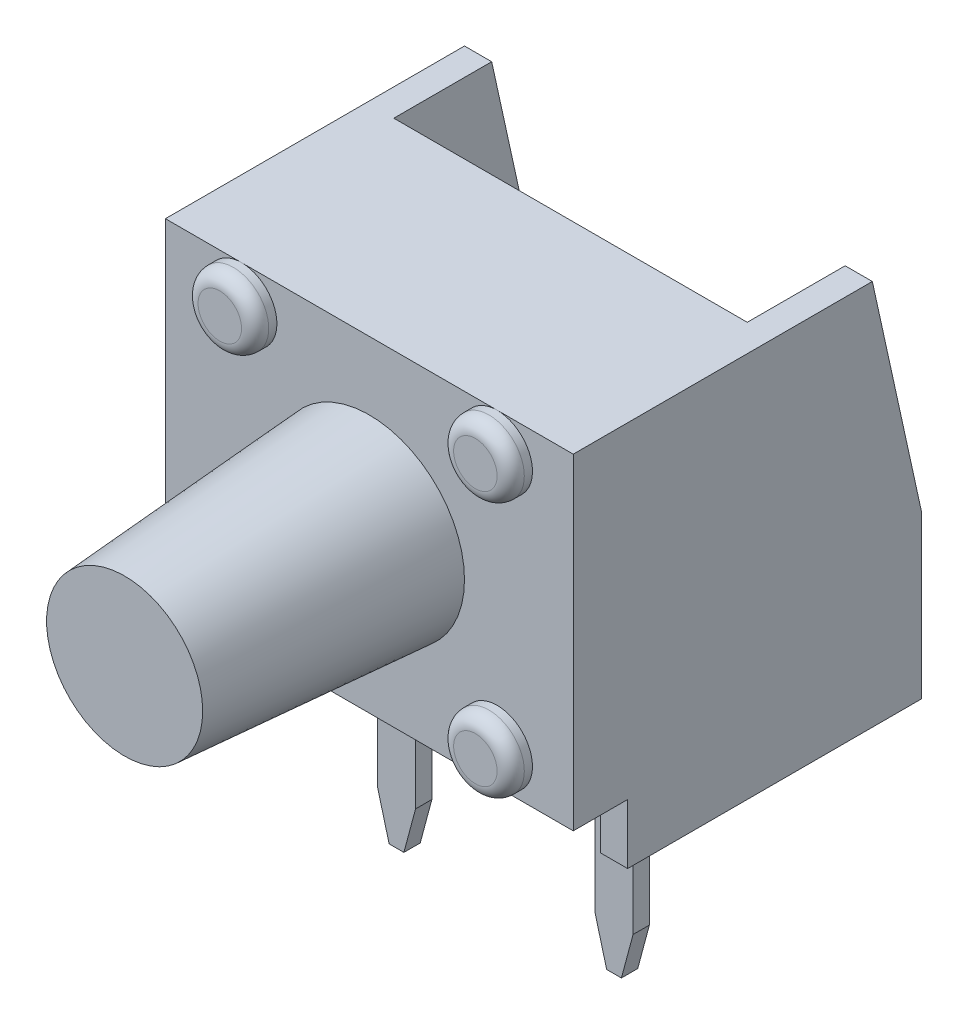
SolidWorks part; units mm, degrees
ref_plane "Front Plane" through (0, 0, 0) normal (0, 0, 1) x (1, 0, 0)
ref_plane "Top Plane" through (0, 0, 0) normal (0, 1, 0) x (1, 0, 0)
ref_plane "Right Plane" through (0, 0, 0) normal (1, 0, 0) x (0, 0, -1)
sketch "Sketch1" plane through (0, 0, 0) normal (0, 1, 0) x (1, 0, 0)
  line L1 (0, 0) -> (7.5, 0)
  line L2 (0, 0) -> (0, 3.7)
  line L3 (0, 3.7) -> (7.5, 3.7)
  line L4 (7.5, 0) -> (7.5, 3.7)
  dimension "D1" = 3.7
  dimension "D2" = 7.5
extrude "Boss-Extrude1" add sketch "Sketch1" along normal blind 6
sketch "Sketch2" plane through (0, 0, 0) normal (0, 0, 1) x (1, 0, 0)
  line L0 (3.75, 6) -> (3.75, 0) construction
  line L1 (0, 6) -> (7.5, 6) construction
  line L2 (0, 0) -> (7.5, 0) construction
  circle A0 centre (3.75, 3) radius 1.75
  dimension "D1" = 3.5
extrude "Boss-Extrude2" add sketch "Sketch2" along normal blind 4.5 draft 4
sketch "Sketch3" plane through (0, 0, 0) normal (0, -1, 0) x (1, 0, 0)
  line L0 (0, 0) -> (7.5, 0) construction
  line L1 (1.4, -2.5) -> (2.1, -2.5)
  line L2 (1.4, -2.5) -> (1.4, -2.8)
  line L3 (1.4, -2.8) -> (2.1, -2.8)
  line L4 (2.1, -2.5) -> (2.1, -2.8)
  line L5 (3.75, 0) -> (3.75, -3.7) construction
  line L6 (5.4, -2.8) -> (6.1, -2.8)
  line L7 (5.4, -2.8) -> (5.4, -2.5)
  line L8 (5.4, -2.5) -> (6.1, -2.5)
  line L9 (6.1, -2.8) -> (6.1, -2.5)
  line L10 (7.5, -3.7) -> (0, -3.7) construction
  line L11 (1.75, -2.5) -> (1.75, -2.8) construction
  line L12 (5.75, -2.5) -> (5.75, -2.8) construction
  line L13 (5.75, -2.65) -> (3.75, -2.65) construction
  line L14 (3.75, -2.65) -> (1.75, -2.65) construction
  dimension "D1" = 2.5
  dimension "D2" = 0.7
  dimension "D3" = 0.3
  dimension "D4" = 2
extrude "Boss-Extrude3" add sketch "Sketch3" along normal blind 4.4
sketch "Sketch4" plane through (0, 0, 0) normal (0, -1, 0) x (1, 0, 0)
  line L0 (0, -3.7) -> (0, -1)
  line L1 (0, -3.7) -> (0, 0) construction
  line L2 (0, -1) -> (0.5, -1)
  line L3 (0.5, -1) -> (0.5, -3.7)
  line L4 (7.5, -3.7) -> (0, -3.7) construction
  line L5 (0.5, -3.7) -> (0, -3.7)
  line L6 (0, 0) -> (7.5, 0) construction
  line L8 (7.5, -3.7) -> (7, -3.7)
  line L9 (7.5, -3.7) -> (7.5, -1)
  line L10 (7.5, -1) -> (7, -1)
  line L11 (7, -3.7) -> (7, -1)
  dimension "D1" = 0.5
  dimension "D2" = 1
  dimension "D3" = 0.5
  dimension "D4" = 1
extrude "Boss-Extrude4" add sketch "Sketch4" along normal blind 1.1
sketch "Sketch5" plane through (0, 0, -3.7) normal (0, 0, -1) x (-1, 0, 0)
  line L0 (-7, 0) -> (-7, 6)
  line L1 (-7.5, 6) -> (0, 6) construction
  line L2 (-7, 6) -> (-7.5, 6)
  line L3 (-7.5, 6) -> (-7.5, -1.1)
  line L4 (-7.5, -1.1) -> (-7, -1.1)
  line L5 (-7, -1.1) -> (-7, 0)
  line L6 (-0.5, -1.1) -> (-0.5, 0)
  line L7 (-0.5, 0) -> (-0.5, 6)
  line L8 (-0.5, 6) -> (0, 6)
  line L9 (0, 6) -> (0, -1.1)
  line L10 (0, -1.1) -> (-0.5, -1.1)
extrude "Boss-Extrude5" add sketch "Sketch5" along normal blind 2.7
sketch "Sketch6" plane through (7.5, 0, 0) normal (1, 0, 0) x (0, 0, -1)
  line L0 (0, 6) -> (5.5, 6) construction
  line L1 (0, 6) -> (6.4, 6) construction
  line L2 (5.5, 6) -> (6.4, 1.9)
  line L3 (6.4, 6) -> (6.4, -1.1) construction
  line L4 (6.4, 1.9) -> (6.4, -1.1) construction
  line L5 (6.4, 1.9) -> (6.4, 6)
  line L6 (6.4, 6) -> (5.5, 6)
  dimension "D1" = 5.5
  dimension "D2" = 3
extrude "Cut-Extrude1" cut sketch "Sketch6" against normal through all
sketch "Sketch7" plane through (0, 0, 0) normal (0, 0, 1) x (1, 0, 0)
  line L0 (7.5, 6) -> (7.5, 0) construction
  line L1 (1.4, 0.65) -> (6.1, 0.65) construction
  line L2 (1.4, 0.65) -> (1.4, 5.35) construction
  line L3 (1.4, 5.35) -> (6.1, 5.35) construction
  line L4 (6.1, 0.65) -> (6.1, 5.35) construction
  line L5 (1.4, 0.65) -> (6.1, 5.35) construction
  line L6 (1.4, 5.35) -> (6.1, 0.65) construction
  line L7 (0, 6) -> (7.5, 6) construction
  circle A0 centre (1.4, 5.35) radius 0.65
  circle A1 centre (6.1, 5.35) radius 0.65
  circle A2 centre (6.1, 0.65) radius 0.65
  circle A3 centre (1.4, 0.65) radius 0.65
  point P0 (3.75, 3)
  dimension "D3" = 1.3
  dimension "D1" = 1.4
  dimension "D2" = 0.65
extrude "Boss-Extrude6" add sketch "Sketch7" along normal blind 0.4
fillet "Fillet1" radius 0.25 4 edges at (2.05, 0.65, 0.4) (2.05, 5.35, 0.4) (6.75, 0.65, 0.4) (6.75, 5.35, 0.4)
chamfer "Chamfer1" distance 0.8 angle 15 4 edges at (1.4, -4.4, -2.65) (2.1, -4.4, -2.65) (6.1, -4.4, -2.65) (5.4, -4.4, -2.65)
